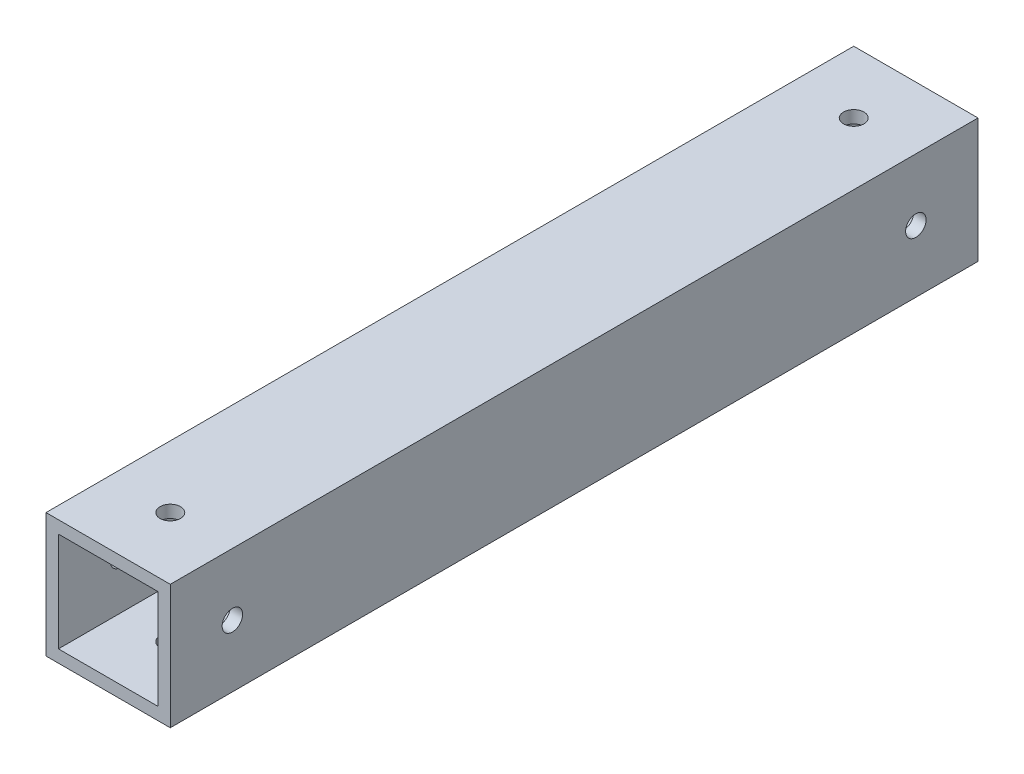
SolidWorks part; units mm, degrees
ref_plane "前视基准面" through (0, 0, 0) normal (0, 0, 1) x (1, 0, 0)
ref_plane "上视基准面" through (0, 0, 0) normal (0, 1, 0) x (1, 0, 0)
ref_plane "右视基准面" through (0, 0, 0) normal (1, 0, 0) x (0, 0, -1)
other "Configuration Table"
sketch "草图1" plane through (0, 0, 0) normal (0, 0, 1) x (1, 0, 0)
  line L1 (-10, -10) -> (10, -10)
  line L2 (-10, -10) -> (-10, 10)
  line L3 (-10, 10) -> (10, 10)
  line L4 (10, -10) -> (10, 10)
  line L5 (-10, -10) -> (10, 10) construction
  line L6 (-10, 10) -> (10, -10) construction
  line L7 (-8, -8) -> (8, -8)
  line L8 (-8, -8) -> (-8, 8)
  line L9 (-8, 8) -> (8, 8)
  line L10 (8, -8) -> (8, 8)
  line L11 (-8, -8) -> (8, 8) construction
  line L12 (-8, 8) -> (8, -8) construction
  point P0 (0, 0)
  point P6 (0, 0)
  dimension "D1" = 20
  dimension "D2" = 20
  dimension "D3" = 2
  dimension "D4" = 2
extrude "凸台-拉伸1" add sketch "草图1" along normal blind 130
sketch "草图2" plane through (0, 10, 0) normal (0, 1, 0) x (1, 0, 0)
  line L0 (0, 0) -> (0, -130) construction
  line L1 (10, 0) -> (-10, 0) construction
  line L2 (10, -130) -> (-10, -130) construction
  line L3 (10, -130) -> (10, 0) construction
  line L5 (-10, -65) -> (10, -65) construction
  line L6 (-10, -130) -> (-10, 0) construction
  circle A0 centre (0, -120) radius 1.65
  circle A1 centre (0, -10) radius 1.65
  point P10 (0, -120)
  dimension "D4" = 3.3
  dimension "D1" = 10
  dimension "D2" = 10
extrude "切除-拉伸1" cut sketch "草图2" against normal blind 30
sketch "草图3" plane through (0, 0, 0) normal (1, 0, 0) x (0, 0, -1)
  line L0 (-130, 0) -> (0, 0) construction
  line L1 (-130, -10) -> (-130, 10) construction
  line L2 (0, -10) -> (0, 10) construction
  circle A0 centre (-120, 0) radius 1.65
  circle A1 centre (-10, 0) radius 1.65
  dimension "D1" = 3.3
  dimension "D3" = 3.3
  dimension "D2" = 10
  dimension "D4" = 10
extrude "切除-拉伸2" cut sketch "草图3" against normal mid plane 20
